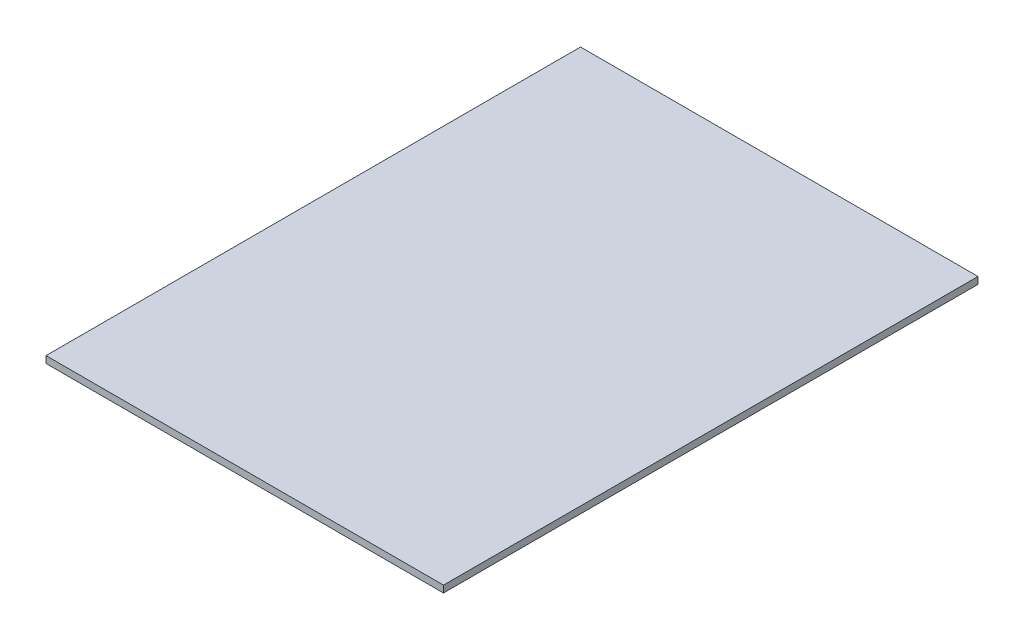
SolidWorks part; units mm, degrees
ref_plane "Front Plane" through (0, 0, 0) normal (0, 0, 1) x (1, 0, 0)
ref_plane "Top Plane" through (0, 0, 0) normal (0, 1, 0) x (1, 0, 0)
ref_plane "Right Plane" through (0, 0, 0) normal (1, 0, 0) x (0, 0, -1)
sketch "Sketch2" plane through (0, 0, 0) normal (0, 1, 0) x (1, 0, 0)
  line L1 (-72.5, 97.5) -> (72.5, 97.5)
  line L2 (-72.5, 97.5) -> (-72.5, -97.5)
  line L3 (-72.5, -97.5) -> (72.5, -97.5)
  line L4 (72.5, 97.5) -> (72.5, -97.5)
  line L5 (-72.5, 97.5) -> (72.5, -97.5) construction
  line L6 (-72.5, -97.5) -> (72.5, 97.5) construction
  point P0 (0, 0)
  dimension "D1" = 145
  dimension "D2" = 195
extrude "Boss-Extrude1" add sketch "Sketch2" along normal mid plane 2.5 contours L2 L1 L4 L3
equation "\"DisplayHeight\"= 18mm"
equation "\"DisplayWidth\"= 93mm"
equation "\"DisplayTall\"= 97mm"
equation "\"boxWidth\" = 15cm"
equation "\"boxTall\" = 20cm"
equation "\"boxHeight\" =68.5cm"
